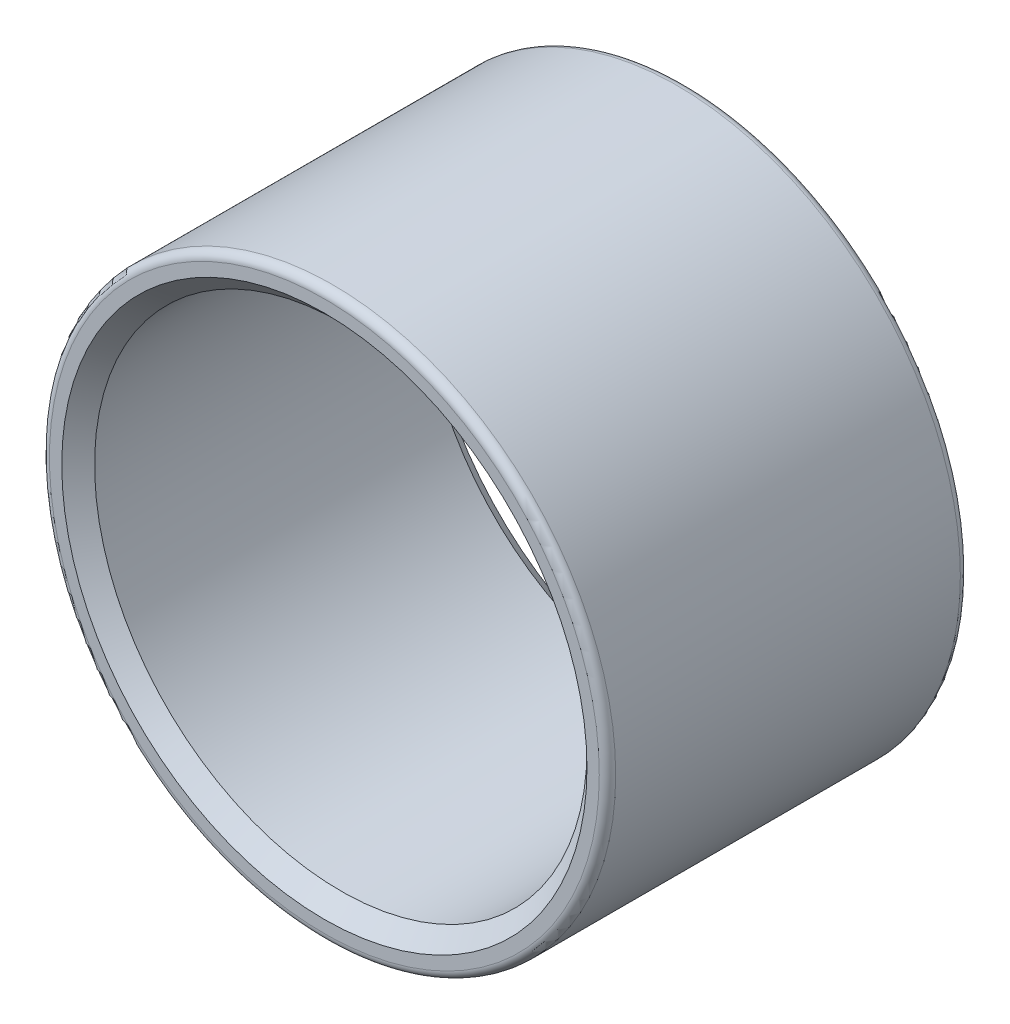
SolidWorks part; units mm, degrees
ref_plane "Plan1" through (0, 0, 0) normal (0, 0, 1) x (1, 0, 0)
ref_plane "Plan2" through (0, 0, 0) normal (0, 1, 0) x (1, 0, 0)
ref_plane "Plan3" through (0, 0, 0) normal (1, 0, 0) x (0, 0, -1)
sketch "Esquisse1" plane through (0, 0, 0) normal (0, 0, 1) x (1, 0, 0)
  circle A0 centre (0, 0) radius 17.25
  circle A1 centre (0, 0) radius 15
  dimension "D1" = 30
  dimension "D2" = 34.5
extrude "Base-Extrusion" add sketch "Esquisse1" along normal blind 22
fillet "Congé1" radius 0.5
chamfer "Chanfrein1" distance 1 angle 45
